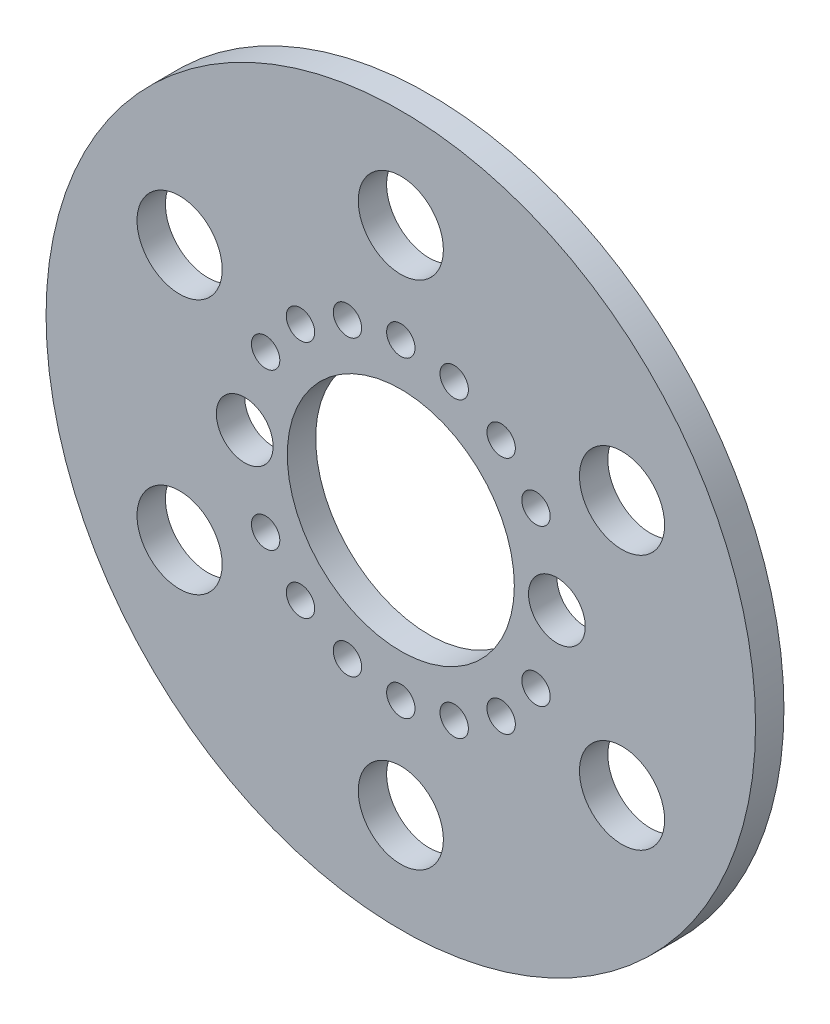
SolidWorks part; units mm, degrees
material "Плата системы питания"
ref_plane "Спереди" through (0, 0, 0) normal (0, 0, 1) x (1, 0, 0)
ref_plane "Сверху" through (0, 0, 0) normal (0, 1, 0) x (1, 0, 0)
ref_plane "Справа" through (0, 0, 0) normal (1, 0, 0) x (0, 0, -1)
sketch "Эскиз1" plane through (0, 0, 0) normal (0, 0, 1) x (1, 0, 0)
  line L0 (0, 0) -> (0, 9) construction
  line L1 (0, 0) -> (0, 5.5) construction
  circle A0 centre (0, 0) radius 4
  circle A1 centre (0, 0) radius 12.5
  circle A2 centre (0, 9) radius 1.5
  circle A3 centre (7.7942, 4.5) radius 1.5
  circle A4 centre (7.7942, -4.5) radius 1.5
  circle A5 centre (0, -9) radius 1.5
  circle A6 centre (-7.7942, -4.5) radius 1.5
  circle A7 centre (-7.7942, 4.5) radius 1.5
  circle A8 centre (-5.5, 0) radius 1
  circle A9 centre (5.5, 0) radius 1
  circle A10 centre (0, 5.5) radius 0.5
  circle A11 centre (1.8811, 5.1683) radius 0.5
  circle A12 centre (3.5353, 4.2132) radius 0.5
  circle A13 centre (4.7631, 2.75) radius 0.5
  circle A14 centre (5.4164, 0.9551) radius 0.5 [skipped]
  circle A15 centre (5.4164, -0.9551) radius 0.5 [skipped]
  circle A16 centre (4.7631, -2.75) radius 0.5
  circle A17 centre (3.5353, -4.2132) radius 0.5
  circle A18 centre (1.8811, -5.1683) radius 0.5
  circle A19 centre (0, -5.5) radius 0.5
  circle A20 centre (-1.8811, -5.1683) radius 0.5
  circle A21 centre (-3.5353, -4.2132) radius 0.5
  circle A22 centre (-4.7631, -2.75) radius 0.5
  circle A23 centre (-5.4164, -0.9551) radius 0.5 [skipped]
  circle A24 centre (-5.4164, 0.9551) radius 0.5 [skipped]
  circle A25 centre (-4.7631, 2.75) radius 0.5
  circle A26 centre (-3.5353, 4.2132) radius 0.5
  circle A27 centre (-1.8811, 5.1683) radius 0.5
  dimension "D1" = 8
  dimension "D2" = 25
  dimension "D3" = 3
  dimension "D8" = 2
  dimension "D9" = 1
  dimension "D13" = 20
  dimension "D4" = 9
  dimension "D6" = 9
  dimension "D7" = 5.5
  dimension "D10" = 5.5
  dimension "D12" = 5.5
  dimension "D5" = 6
  dimension "D11" = 18
extrude "Бобышка-Вытянуть1" add sketch "Эскиз1" along normal blind 1
